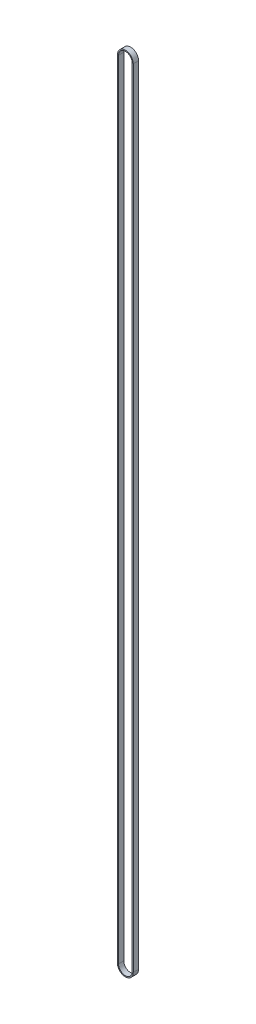
SolidWorks part; units mm, degrees
ref_plane "前基準面" through (0, 0, 0) normal (0, 0, 1) x (1, 0, 0)
ref_plane "上基準面" through (0, 0, 0) normal (0, 1, 0) x (1, 0, 0)
ref_plane "右基準面" through (0, 0, 0) normal (1, 0, 0) x (0, 0, -1)
sketch "草圖1" plane through (0, 0, 0) normal (0, 0, 1) x (1, 0, 0)
  line L0 (0, 0) -> (0, 57.0517) construction
  line L1 (6.5, 753.5) -> (6.5, 6.5)
  line L2 (-6.5, 753.5) -> (-6.5, 6.5)
  line L3 (7.5, 753.5) -> (7.5, 6.5)
  line L4 (-7.5, 753.5) -> (-7.5, 6.5)
  arc A0 (6.5, 753.5) -> (-6.5, 753.5) centre (0, 753.5) ccw
  arc A1 (6.5, 6.5) -> (-6.5, 6.5) centre (0, 6.5) cw
  arc A2 (7.5, 6.5) -> (-7.5, 6.5) centre (0, 6.5) cw
  arc A3 (7.5, 753.5) -> (-7.5, 753.5) centre (0, 753.5) ccw
  dimension "D2" = 760
  dimension "D1" = 13
  dimension "D3" = 1
extrude "填料-伸長1" add sketch "草圖1" along normal blind 5
